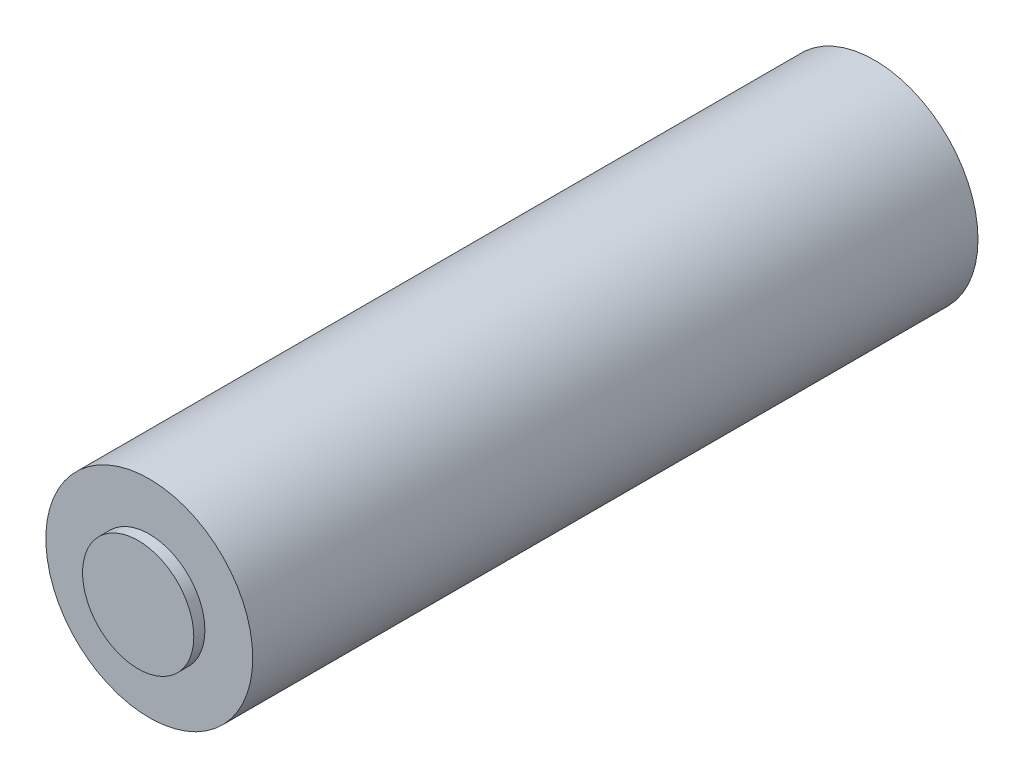
SolidWorks part; units mm, degrees
ref_plane "Front Plane" through (0, 0, 0) normal (0, 0, 1) x (1, 0, 0)
ref_plane "Top Plane" through (0, 0, 0) normal (0, 1, 0) x (1, 0, 0)
ref_plane "Right Plane" through (0, 0, 0) normal (1, 0, 0) x (0, 0, -1)
sketch "Sketch1" plane through (0, 0, 0) normal (0, 0, 1) x (1, 0, 0)
  circle A0 centre (0, 0) radius 9.3
  dimension "D1" = 18.6
extrude "Boss-Extrude1" add sketch "Sketch1" along normal blind 65.2
sketch "Sketch2" plane through (0, 0, 65.2) normal (0, 0, 1) x (1, 0, 0)
  circle A0 centre (0, 0) radius 5
  circle A1 centre (0, 0) radius 9.3 construction
  dimension "D1" = 10
extrude "Boss-Extrude2" add sketch "Sketch2" along normal blind 1
ref_plane "Plane1" through (0, 0, 0) normal (0, 1, 0) x (1, 0, 0)
ref_plane "Plane2" through (0, 0, 0) normal (1, 0, 0) x (0, 0, -1)
